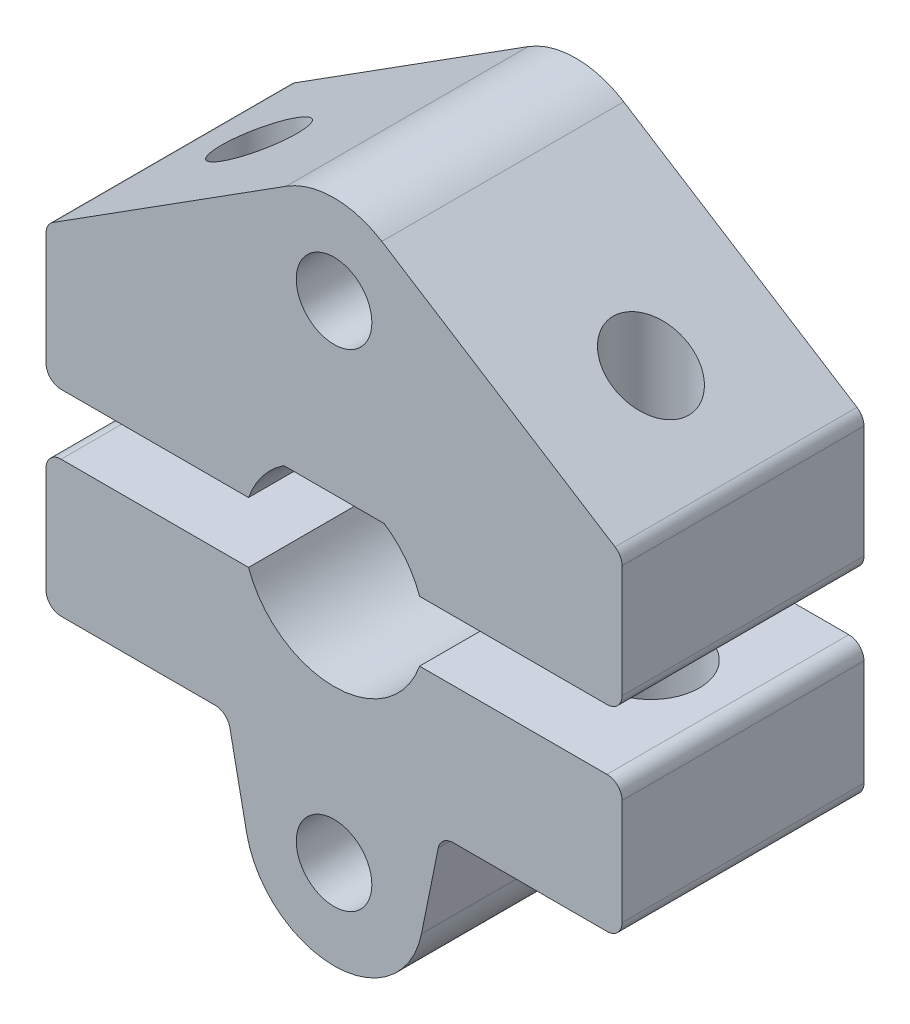
SolidWorks part; units mm, degrees
material "6061-T6 (SS)"
ref_plane "前视基准面" through (0, 0, 0) normal (0, 0, 1) x (1, 0, 0)
ref_plane "上视基准面" through (0, 0, 0) normal (0, 1, 0) x (1, 0, 0)
ref_plane "右视基准面" through (0, 0, 0) normal (1, 0, 0) x (0, 0, -1)
sketch "草图1" plane through (0, 0, 0) normal (0, 0, 1) x (1, 0, 0)
  line L0 (-1.6583, 2.5) -> (1.6583, 2.5)
  line L1 (-9.2941, 5.6473) -> (-1.5803, 10.541)
  line L2 (1.5803, 10.541) -> (9.2941, 5.6473)
  line L3 (-9.5263, 5.2251) -> (-9.5263, 1.5)
  line L4 (-9.0263, 1) -> (-2.8284, 1)
  line L5 (9.5263, 1.5) -> (9.5263, 5.2251)
  line L6 (0, 1) -> (0, 0) construction
  line L7 (-9.0263, -1) -> (-2.8284, -1)
  line L8 (9.5263, -1.5) -> (9.5263, -5)
  line L9 (9.0263, -5.5) -> (3.9352, -5.5)
  line L10 (3.4451, -5.9008) -> (2.8913, -8.6355)
  line L11 (-2.8913, -8.6355) -> (-3.4451, -5.9008)
  line L12 (-3.9352, -5.5) -> (-9.0263, -5.5)
  line L13 (-9.5263, -5) -> (-9.5263, -1.5)
  line L14 (0, 0) -> (0, -1) construction
  line L15 (2.8284, 1) -> (9.0263, 1)
  line L16 (2.8284, -1) -> (9.0263, -1)
  line L17 (9.2941, 5.6473) -> (9.5263, 5.5) construction
  line L18 (9.5263, 5.5) -> (9.5263, 5.2251) construction
  arc A0 (-1.6583, 2.5) -> (-2.8284, 1) centre (0, 0) ccw
  circle A1 centre (0, 0) radius 8.05 construction
  circle A2 centre (0, 8.05) radius 1.25
  circle A3 centre (0, -8.05) radius 1.25
  arc A4 (-1.5803, 10.541) -> (1.5803, 10.541) centre (0, 8.05) cw
  circle A5 centre (0, 0) radius 11 construction
  arc A6 (2.8913, -8.6355) -> (-2.8913, -8.6355) centre (0, -8.05) cw
  arc A7 (-9.5263, 1.5) -> (-9.0263, 1) centre (-9.0263, 1.5) ccw
  arc A8 (-9.2941, 5.6473) -> (-9.5263, 5.2251) centre (-9.0263, 5.2251) ccw
  arc A9 (9.2941, 5.6473) -> (9.5263, 5.2251) centre (9.0263, 5.2251) cw
  arc A10 (9.0263, 1) -> (9.5263, 1.5) centre (9.0263, 1.5) ccw
  arc A11 (-9.0263, -5.5) -> (-9.5263, -5) centre (-9.0263, -5) cw
  arc A12 (-9.0263, -1) -> (-9.5263, -1.5) centre (-9.0263, -1.5) ccw
  arc A13 (9.5263, -5) -> (9.0263, -5.5) centre (9.0263, -5) cw
  arc A14 (9.0263, -1) -> (9.5263, -1.5) centre (9.0263, -1.5) cw
  arc A15 (3.9352, -5.5) -> (3.4451, -5.9008) centre (3.9352, -6) ccw
  arc A16 (-3.4451, -5.9008) -> (-3.9352, -5.5) centre (-3.9352, -6) ccw
  arc A17 (-2.8284, -1) -> (2.8284, -1) centre (0, 0) ccw
  arc A18 (2.8284, 1) -> (1.6583, 2.5) centre (0, 0) ccw
  point P31 (-9.5263, 1)
  point P34 (-9.5263, 5.5)
  point P39 (9.5263, 1)
  point P42 (-9.5263, -5.5)
  point P47 (9.5263, -5.5)
  point P52 (3.5263, -5.5)
  dimension "D1" = 16.1
  dimension "D2" = 6
  dimension "D4" = 2.5
  dimension "D6" = 22
  dimension "D10" = 0.5
  dimension "D5" = 4.5
  dimension "D3" = 2.5
  dimension "D7" = 1
  dimension "D9" = 6
extrude "凸台-拉伸1" add sketch "草图1" along normal blind 8
cosmetic thread "装饰螺纹线3" parameters "D2"=3
cosmetic thread "装饰螺纹线4" parameters "D2"=3
sketch "草图2" plane through (0, -5.5, 0) normal (0, -1, 0) x (1, 0, 0)
  line L0 (-9.5263, 4) -> (-6.4807, 4) construction
  line L1 (-9.5263, 8) -> (-9.5263, 0) construction
  line L2 (-6.4807, 4) -> (6.4807, 4) construction
  line L3 (6.4807, 4) -> (9.5263, 4) construction
  line L4 (9.5263, 8) -> (9.5263, 0) construction
  line L5 (6.4807, 8) -> (6.4807, 4) construction
  line L6 (3.9352, 8) -> (9.0263, 8) construction
  circle A0 centre (6.4807, 4) radius 1.25
  circle A1 centre (-6.4807, 4) radius 1.25
  dimension "D1" = 2.5
extrude "切除-拉伸1" cut sketch "草图2" against normal through all
cosmetic thread "装饰螺纹线1" parameters "D2"=3
cosmetic thread "装饰螺纹线2" parameters "D2"=3
sketch "草图3" plane through (0, -5.5, 0) normal (0, -1, 0) x (1, 0, 0)
  circle A0 centre (-6.4807, 4) radius 1.6
  circle A1 centre (6.4807, 4) radius 1.6
  dimension "D1" = 3.2
extrude "切除-拉伸2" cut sketch "草图3" against normal up to surface (4.5 mm away) up to face at (-5.2307, -1, 4)
